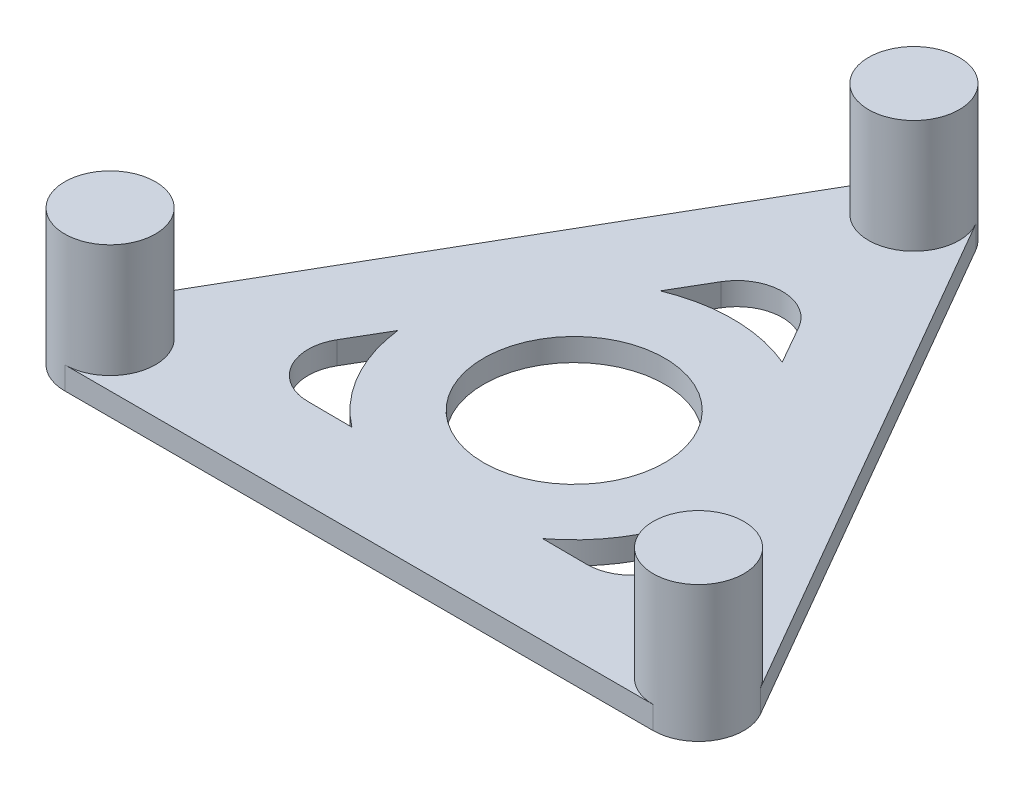
SolidWorks part; units mm, degrees
ref_plane "Front Plane" through (0, 0, 0) normal (0, 0, 1) x (1, 0, 0)
ref_plane "Top Plane" through (0, 0, 0) normal (0, 1, 0) x (1, 0, 0)
ref_plane "Right Plane" through (0, 0, 0) normal (1, 0, 0) x (0, 0, -1)
sketch "Sketch1" plane through (0, 0, 0) normal (0, 1, 0) x (1, 0, 0)
  line L0 (-14.7239, -6.4992) -> (-1.7335, 16.0008)
  line L1 (-7.9369, -2.5277) -> (-6.9494, -0.8401)
  line L2 (1.7794, 8.1374) -> (2.7472, 6.4384)
  line L3 (1.7335, 16.0008) -> (14.7239, -6.4992)
  line L4 (6.1575, -5.6097) -> (4.2022, -5.5983)
  line L5 (12.9904, -9.5017) -> (-12.9904, -9.5017)
  line L6 (-8.2287, 4.7508) -> (0, 0) construction
  line L7 (0, 0) -> (0, 17.0017) construction
  line L8 (8.2287, 4.7508) -> (0, 0) construction
  line L9 (0, 0) -> (14.7239, -8.5008) construction
  line L10 (0, -9.5017) -> (0, 0) construction
  line L11 (0, 0) -> (-14.7239, -8.5008) construction
  line L12 (-4.2671, -5.5491) -> (-6.2223, -5.5377)
  line L13 (-2.6721, 6.4699) -> (-1.6846, 8.1575)
  line L14 (6.9392, -0.9209) -> (7.9069, -2.6198)
  circle A0 centre (0, 0) radius 15 construction
  circle A1 centre (0, 0) radius 17.2 construction
  circle A2 centre (0, 15) radius 2.0017
  circle A5 centre (12.9904, -7.5) radius 2.0017
  circle A6 centre (-12.9904, -7.5) radius 2.0017
  arc A7 (-6.2223, -5.5377) -> (-7.9369, -2.5277) centre (-6.2107, -3.5377) cw
  arc A8 (1.7794, 8.1374) -> (-1.6846, 8.1575) centre (0.0416, 7.1475) ccw
  arc A9 (6.1575, -5.6097) -> (7.9069, -2.6198) centre (6.1691, -3.6097) ccw
  circle A11 centre (0, 0) radius 4
  arc A12 (2.7472, 6.4384) -> (-2.6721, 6.4699) centre (0, 0) ccw
  arc A13 (-6.9494, -0.8401) -> (-4.2671, -5.5491) centre (0, 0) ccw
  arc A14 (4.2022, -5.5983) -> (6.9392, -0.9209) centre (0, 0) ccw
  point P13 (0, 0)
  point P26 (0, 0)
  point P37 (0, 0)
  dimension "D1" = 30
  dimension "D2" = 34.4
  dimension "D3" = 4.0033
  dimension "D5" = 2
  dimension "D6" = 2
  dimension "D7" = 3
  dimension "D8" = 8
  dimension "D9" = 14
  dimension "D10" = 2.2
  dimension "D11" = 8
  dimension "D12" = 8
  dimension "D13" = 8
  dimension "D4" = 3
extrude "Boss-Extrude1" add sketch "Sketch1" along normal blind 1 contours A6 L5 A5 L3 A2 L0 A11 L2 A12 L13 A8 L1 A13 L12 A7 L4 A14 L14 A9
sketch "Sketch3" plane through (0, 0, 0) normal (0, -1, 0) x (1, 0, 0)
  circle A0 centre (-12.9904, 7.5) radius 2.0017
  circle A1 centre (12.9904, 7.5) radius 2.0017
  circle A2 centre (0, -15) radius 2.0017
extrude "Boss-Extrude2" add sketch "Sketch3" against normal blind 6
